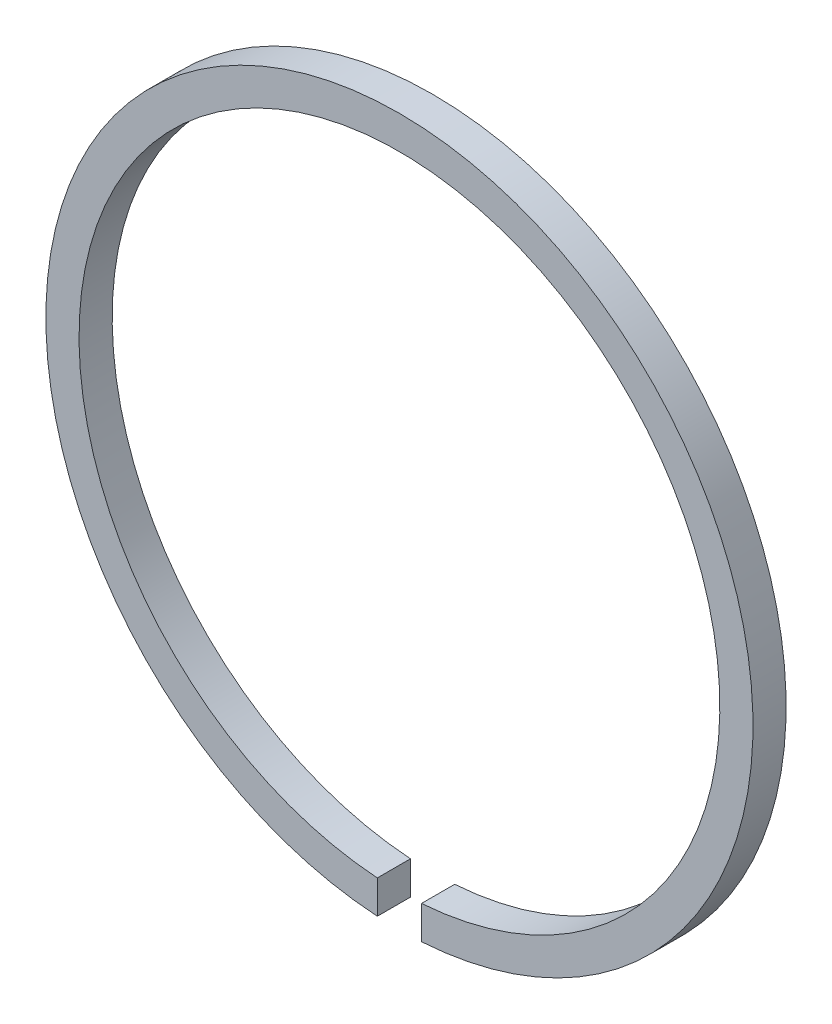
SolidWorks part; units mm, degrees
ref_plane "Front Plane" through (0, 0, 0) normal (0, 0, 1) x (1, 0, 0)
ref_plane "Top Plane" through (0, 0, 0) normal (0, 1, 0) x (1, 0, 0)
ref_plane "Right Plane" through (0, 0, 0) normal (1, 0, 0) x (0, 0, -1)
sketch "Sketch1" plane through (0, 0, 0) normal (0, 0, 1) x (1, 0, 0)
  line L0 (0, 0) -> (0, -16) construction
  line L1 (-1, -14.4655) -> (-1, -15.9687)
  line L2 (1, -14.4655) -> (1, -15.9687)
  line L4 (1, 0) -> (1, -16) construction
  line L5 (-1, 0) -> (-1, -16) construction
  arc A0 (1, -15.9687) -> (-1, -15.9687) centre (0, 0) ccw
  arc A1 (1, -14.4655) -> (-1, -14.4655) centre (0, 0) ccw
  dimension "D1" = 32
  dimension "D2" = 29
  dimension "D3" = 1
  dimension "D4" = 1
extrude "Boss-Extrude1" add sketch "Sketch1" along normal mid plane 1.5
